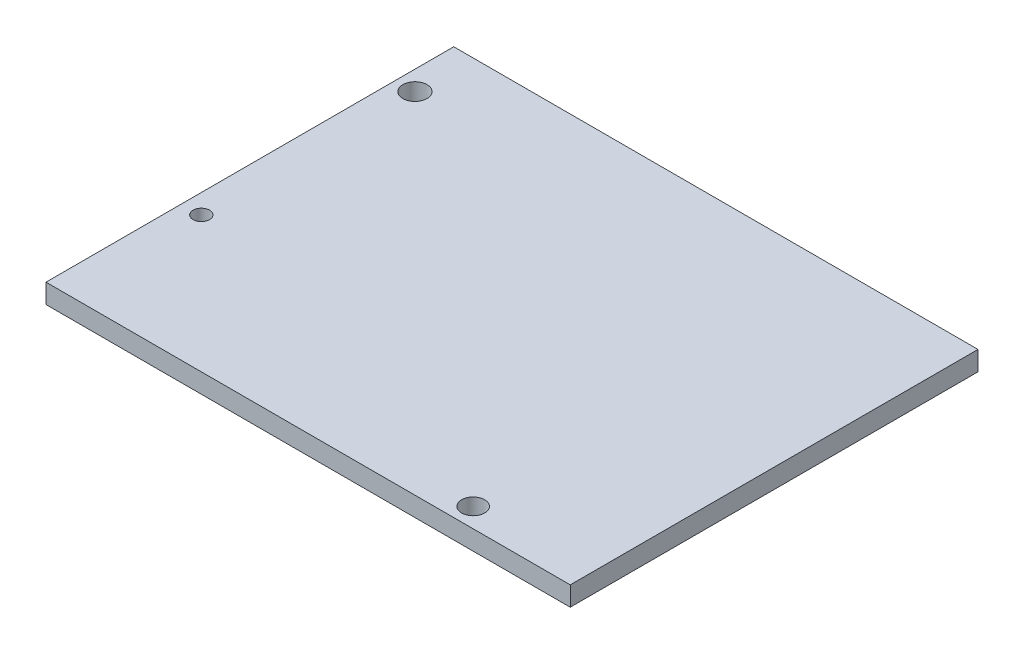
SolidWorks part; units mm, degrees
ref_plane "Front Plane" through (0, 0, 0) normal (0, 0, 1) x (1, 0, 0)
ref_plane "Top Plane" through (0, 0, 0) normal (0, 1, 0) x (1, 0, 0)
ref_plane "Right Plane" through (0, 0, 0) normal (1, 0, 0) x (0, 0, -1)
sketch "Sketch1" plane through (0, 0, 0) normal (0, 1, 0) x (1, 0, 0)
  line L1 (2.2626, 9.4853) -> (70.8426, 9.4853)
  line L2 (2.2626, 9.4853) -> (2.2626, -43.8547)
  line L3 (2.2626, -43.8547) -> (70.8426, -43.8547)
  line L4 (70.8426, 9.4853) -> (70.8426, -43.8547)
  circle A0 centre (4.8026, 1.8653) radius 1.5835
  circle A1 centre (55.6026, -41.3147) radius 1.5071
  circle A2 centre (4.8026, -26.0747) radius 1.0795
  dimension "D3" = 2.54
  dimension "D1" = 53.34
  dimension "D2" = 68.58
  dimension "D4" = 2.54
  dimension "D5" = 2.54
  dimension "D6" = 15.2401
  dimension "D7" = 17.78
  dimension "D8" = 45.72
sketch "Sketch2" plane through (0, 0, 0) normal (0, 1, 0) x (1, 0, 0)
  line L0 (2.2626, 9.4853) -> (70.8426, 9.4853)
  line L1 (2.2626, 9.4853) -> (2.2626, -43.8547)
  line L2 (2.2626, -43.8547) -> (70.8426, -43.8547)
  line L3 (70.8426, 9.4853) -> (70.8426, -43.8547)
  circle A0 centre (4.8026, 1.8653) radius 1.5835
  circle A1 centre (55.6026, -41.3147) radius 1.5071
  circle A2 centre (4.8026, -26.0747) radius 1.0795
  dimension "D1" = 2.54
  dimension "D2" = 2.54
  dimension "D3" = 2.54
  dimension "D4" = 15.2401
  dimension "D5" = 17.78
  dimension "D6" = 45.72
extrude "Extrude1" add sketch "Sketch2" along normal blind 2.54
